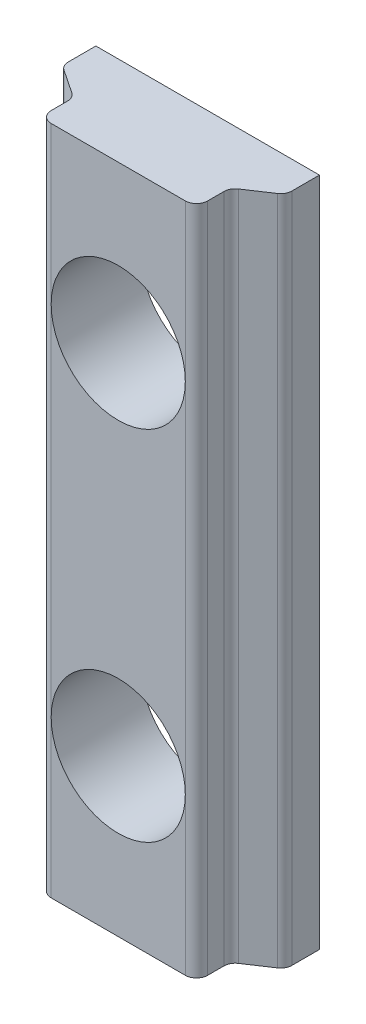
SolidWorks part; units mm, degrees
ref_plane "Спереди" through (0, 0, 0) normal (0, 0, 1) x (1, 0, 0)
ref_plane "Сверху" through (0, 0, 0) normal (0, 1, 0) x (1, 0, 0)
ref_plane "Справа" through (0, 0, 0) normal (1, 0, 0) x (0, 0, -1)
sketch "Эскиз1" plane through (0, 0, 0) normal (0, 1, 0) x (1, 0, 0)
  line L0 (-5, 0) -> (5, 0)
  line L1 (5, -1.5) -> (3.5, -2.5)
  line L2 (3.5, -2.5) -> (3.5, -4)
  line L3 (3.5, -4) -> (-3.5, -4)
  line L4 (-3.5, -4) -> (-3.5, -2.5)
  line L5 (-3.5, -2.5) -> (-5, -1.5)
  line L6 (-5, -1.5) -> (-5, 0)
  line L7 (5, 0) -> (5, -1.5)
  dimension "D1" = 10
  dimension "D2" = 5
  dimension "D3" = 4
  dimension "D4" = 1.5
  dimension "D5" = 1.5
  dimension "D6" = 7
extrude "Бобышка-Вытянуть1" add sketch "Эскиз1" along normal blind 30
fillet "Скругление1" radius 0.5 6 edges at (5, 15, 1.5) (-5, 15, 1.5) (-3.5, 15, 2.5) (3.5, 15, 2.5) (-3.5, 15, 4) (3.5, 15, 4)
sketch "Эскиз2" plane through (0, 0, 4) normal (0, 0, 1) x (1, 0, 0)
  line L0 (-3, 30) -> (3, 30) construction
  circle A0 centre (0, 23) radius 3
  circle A1 centre (0, 7) radius 3
  dimension "D1" = 6
  dimension "D2" = 6
  dimension "D3" = 16
  dimension "D4" = 7
extrude "Вырез-Вытянуть1" cut sketch "Эскиз2" against normal blind 30
cosmetic thread "Условное изображение резьбы1" parameters "D2"=18
cosmetic thread "Условное изображение резьбы2" parameters "D2"=18
